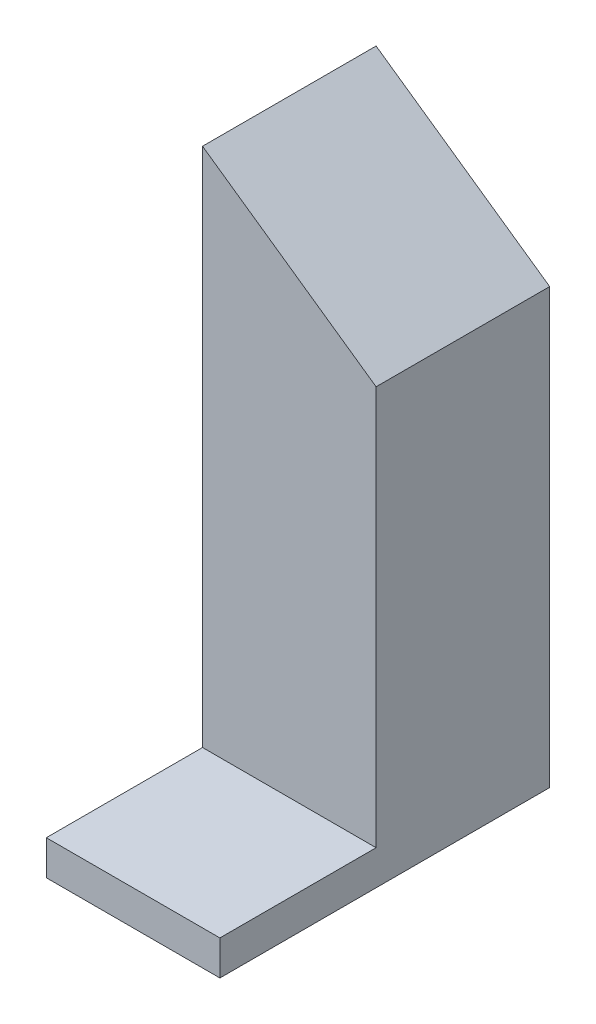
SolidWorks part; units mm, degrees
ref_plane "Front Plane" through (0, 0, 0) normal (0, 0, 1) x (1, 0, 0)
ref_plane "Top Plane" through (0, 0, 0) normal (0, 1, 0) x (1, 0, 0)
ref_plane "Right Plane" through (0, 0, 0) normal (1, 0, 0) x (0, 0, -1)
sketch "Sketch1" plane through (0, 0, 0) normal (0, 0, 1) x (1, 0, 0)
  line L0 (0, 0) -> (0, 5)
  line L5 (0, 5) -> (5, 1.499)
  line L9 (0, 0) -> (0, -10)
  line L10 (0, -10) -> (5, -10)
  line L11 (5, 1.499) -> (5, -10)
  dimension "D1" = 5
  dimension "D2" = 55
  dimension "D3" = 10
  dimension "D4" = 5
extrude "Boss-Extrude1" add sketch "Sketch1" along normal blind 5
sketch "Sketch2" plane through (0, -10, 0) normal (0, -1, 0) x (1, 0, 0)
  line L6 (0, 5) -> (5, 5) construction
  line L7 (0, 0) -> (5, 0)
  line L8 (0, 0) -> (0, 9.5)
  line L9 (0, 9.5) -> (5, 9.5)
  line L10 (5, 0) -> (5, 9.5)
  dimension "D1" = 4.5
extrude "Boss-Extrude2" add sketch "Sketch2" along normal blind 1
